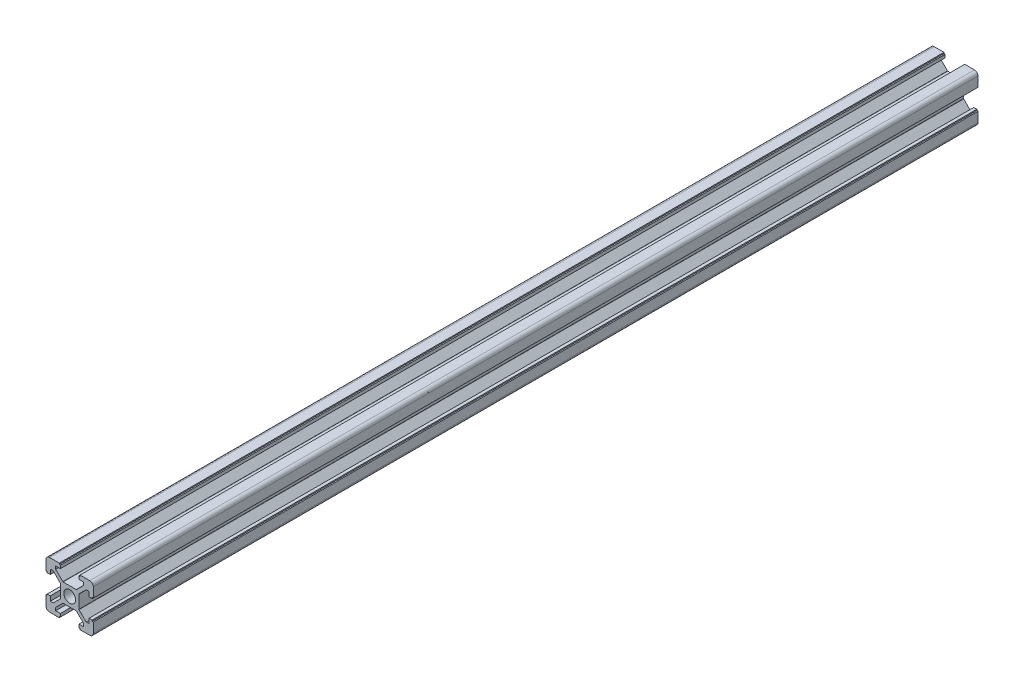
SolidWorks part; units mm, degrees
ref_plane "前视基准面" through (0, 0, 0) normal (0, 0, 1) x (1, 0, 0)
ref_plane "上视基准面" through (0, 0, 0) normal (0, 1, 0) x (1, 0, 0)
ref_plane "右视基准面" through (0, 0, 0) normal (1, 0, 0) x (0, 0, -1)
other "Configuration Table"
sketch "草图1" plane through (0, 0, 0) normal (0, 0, 1) x (1, 0, 0)
  line L0 (-10, 0) -> (10, 0) construction
  line L1 (-10, 10) -> (-4.3839, 10)
  line L2 (-10, 10) -> (-10, 4.3839)
  line L3 (-10, -10) -> (-4.3839, -10)
  line L4 (10, 10) -> (10, 4.3839)
  line L5 (-10, 10) -> (10, -10) construction
  line L6 (-10, -10) -> (10, 10) construction
  line L7 (-2.8396, 3.9001) -> (2.8395, 3.9001)
  line L8 (-3.9, 2.8393) -> (-3.9, -2.8395)
  line L9 (-2.8393, -3.9) -> (2.8395, -3.9)
  line L10 (3.9001, 2.8396) -> (3.9001, -2.8395)
  line L11 (-3.9, 3.9) -> (3.9, -3.9) construction
  line L12 (-3.9, -3.9) -> (3.9, 3.9) construction
  line L13 (0, 10) -> (0, -10) construction
  line L14 (-6.9607, 5.9) -> (-3.9, 2.8393)
  line L15 (-5.9, 6.9607) -> (-2.8396, 3.9001)
  line L16 (-6.9607, 5.9) -> (-8.2, 5.9)
  line L17 (-8.2, 5.9) -> (-8.2, 3.9)
  line L18 (-8.2, 3.9) -> (-9.5003, 3.9)
  line L19 (-9.5003, 3.9) -> (-9.5003, 4.4)
  line L20 (-9.5003, 4.4) -> (-10, 4.3839)
  line L21 (-5.9, 6.9607) -> (-5.9, 8.2)
  line L22 (-5.9, 8.2) -> (-3.9, 8.2)
  line L23 (-3.9, 8.2) -> (-3.9, 9.5003)
  line L24 (-3.9, 9.5003) -> (-4.4, 9.5003)
  line L25 (-4.4, 9.5003) -> (-4.3839, 10)
  line L26 (6.9607, 5.9) -> (3.9001, 2.8396)
  line L27 (5.9, 6.9607) -> (2.8393, 3.9)
  line L28 (5.9, 6.9607) -> (5.9, 8.2)
  line L29 (5.9, 8.2) -> (3.9, 8.2)
  line L30 (3.9, 8.2) -> (3.9, 9.5003)
  line L31 (3.9, 9.5003) -> (4.4, 9.5003)
  line L32 (4.4, 9.5003) -> (4.3839, 10)
  line L33 (6.9607, 5.9) -> (8.2, 5.9)
  line L34 (8.2, 5.9) -> (8.2, 3.9)
  line L35 (8.2, 3.9) -> (9.5003, 3.9)
  line L36 (9.5003, 3.9) -> (9.5003, 4.4)
  line L37 (9.5003, 4.4) -> (10, 4.3839)
  line L38 (5.9, -6.9607) -> (2.8395, -3.9)
  line L39 (6.9607, -5.9) -> (3.9, -2.8393)
  line L40 (6.9607, -5.9) -> (8.2, -5.9)
  line L41 (8.2, -5.9) -> (8.2, -3.9)
  line L42 (8.2, -3.9) -> (9.5003, -3.9)
  line L43 (9.5003, -3.9) -> (9.5003, -4.4)
  line L44 (9.5003, -4.4) -> (10, -4.3839)
  line L45 (5.9, -6.9607) -> (5.9, -8.2)
  line L46 (5.9, -8.2) -> (3.9, -8.2)
  line L47 (3.9, -8.2) -> (3.9, -9.5003)
  line L48 (3.9, -9.5003) -> (4.4, -9.5003)
  line L49 (4.4, -9.5003) -> (4.3839, -10)
  line L50 (-6.9607, -5.9) -> (-3.9, -2.8395)
  line L51 (-5.9, -6.9607) -> (-2.8393, -3.9)
  line L52 (-5.9, -6.9607) -> (-5.9, -8.2)
  line L53 (-5.9, -8.2) -> (-3.9, -8.2)
  line L54 (-3.9, -8.2) -> (-3.9, -9.5003)
  line L55 (-3.9, -9.5003) -> (-4.4, -9.5003)
  line L56 (-4.4, -9.5003) -> (-4.3839, -10)
  line L57 (-6.9607, -5.9) -> (-8.2, -5.9)
  line L58 (-8.2, -5.9) -> (-8.2, -3.9)
  line L59 (-8.2, -3.9) -> (-9.5003, -3.9)
  line L60 (-9.5003, -3.9) -> (-9.5003, -4.4)
  line L61 (-9.5003, -4.4) -> (-10, -4.3839)
  line L62 (4.3839, -10) -> (10, -10)
  line L63 (-10, -4.3839) -> (-10, -10)
  line L64 (10, -10) -> (10, -4.3839)
  line L65 (4.3839, 10) -> (10, 10)
  circle A0 centre (0, 0) radius 2.5
  point P0 (0, 0)
  point P6 (0, 0)
  point P18 (-31.5626, 10.0647)
  point P76 (0, 0)
  dimension "D6" = 5
  dimension "D1" = 20
  dimension "D3" = 7.8
  dimension "D4" = 7.8
  dimension "D5" = 0.75
  dimension "D7" = 0.5
  dimension "D8" = 0.5
  dimension "D9" = 1.8
  dimension "D10" = 6.1
  dimension "D12" = 2
  dimension "D11" = 4
extrude "凸台-拉伸1" add sketch "草图1" along normal blind 374
fillet "圆角1" radius 1.5 4 edges at (10, -10, 187) (-10, -10, 187) (-10, 10, 187) (10, 10, 187)
fillet "圆角2" radius 0.2 8 edges at (3.9001, -2.8395, 187) (3.9001, 2.8396, 187) (-2.8393, -3.9, 187) (2.8395, -3.9, 187) (-2.8396, 3.9001, 187) (2.8395, 3.9001, 187) (-3.9, 2.8393, 187) (-3.9, -2.8395, 187)
